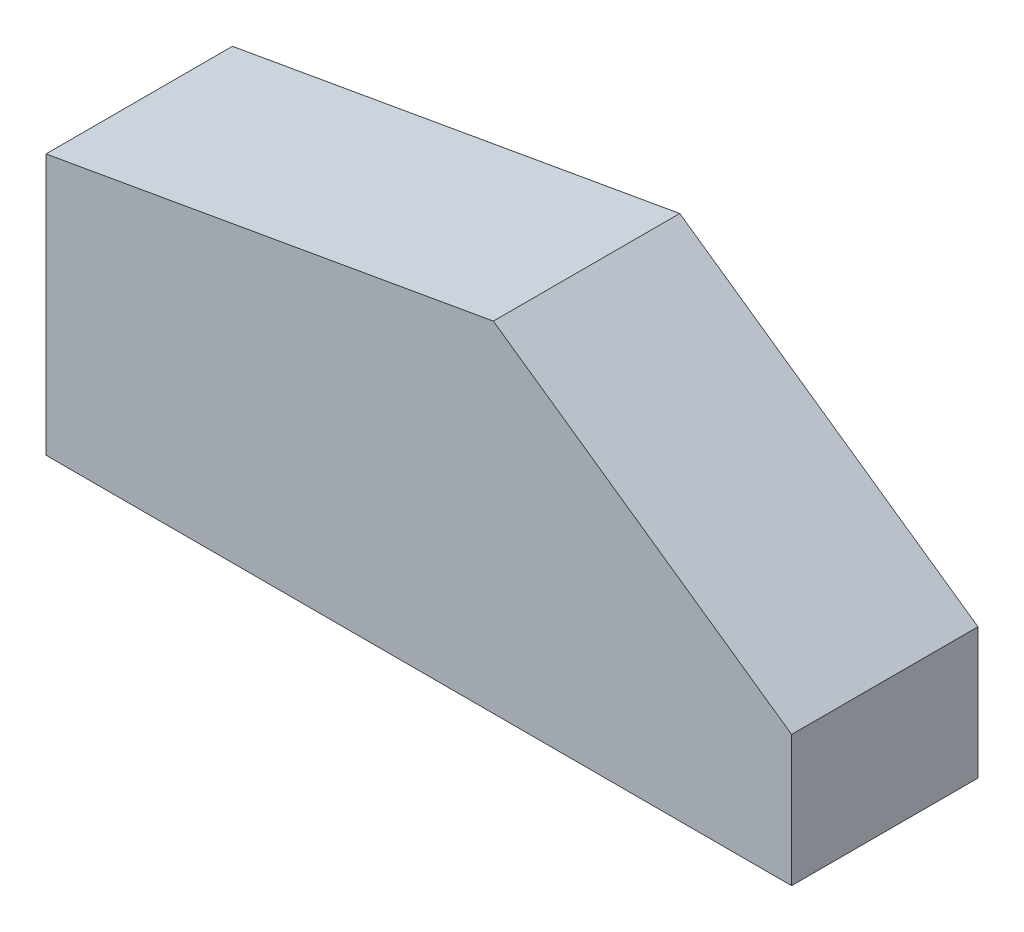
SolidWorks part; units mm, degrees
ref_plane "Front Plane" through (0, 0, 0) normal (0, 0, 1) x (1, 0, 0)
ref_plane "Top Plane" through (0, 0, 0) normal (0, 1, 0) x (1, 0, 0)
ref_plane "Right Plane" through (0, 0, 0) normal (1, 0, 0) x (0, 0, -1)
sketch "Sketch3" plane through (0, 0, 0) normal (0, 0, 1) x (1, 0, 0)
  line L0 (-25, 95) -> (-25, 130)
  line L1 (-25, 95) -> (75, 95)
  line L2 (75, 95) -> (75, 112.5713)
  line L3 (75, 112.5713) -> (35, 140.5796)
  line L4 (35, 140.5796) -> (-25, 130)
  dimension "D1" = 60
  dimension "D2" = 100
  dimension "D3" = 135
  dimension "D4" = 100
  dimension "D5" = 35
extrude "Boss-Extrude1" add sketch "Sketch3" along normal blind 25 contours L4 L0 L1 L2 L3
